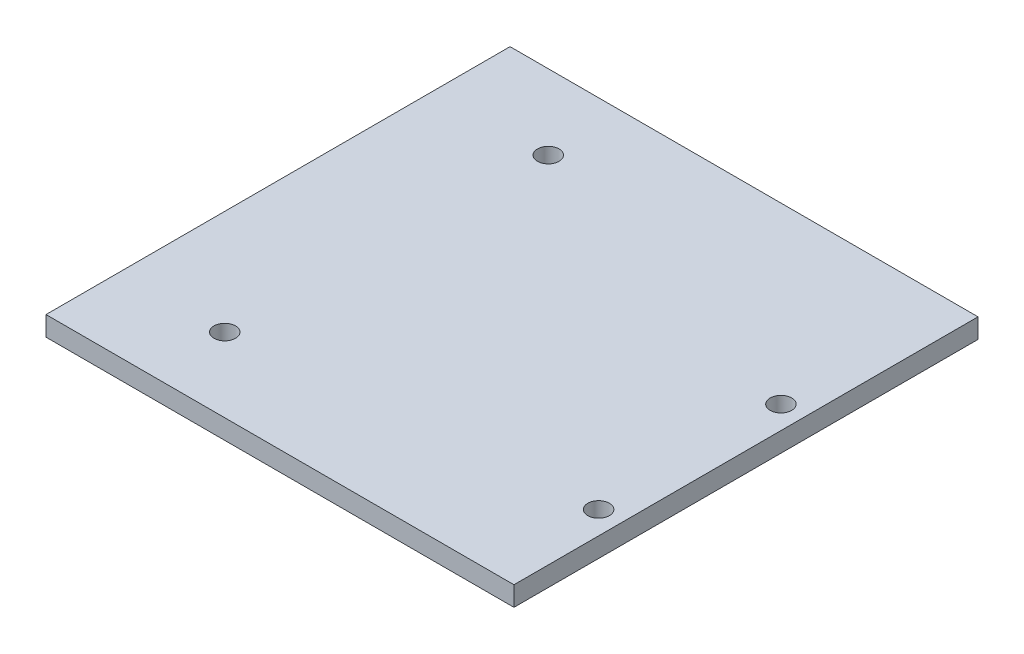
SolidWorks part; units mm, degrees
ref_plane "Front Plane" through (0, 0, 0) normal (0, 0, 1) x (1, 0, 0)
ref_plane "Top Plane" through (0, 0, 0) normal (0, 1, 0) x (1, 0, 0)
ref_plane "Right Plane" through (0, 0, 0) normal (1, 0, 0) x (0, 0, -1)
sketch "Sketch1" plane through (0, 0, 0) normal (0, 1, 0) x (1, 0, 0)
  line L1 (1.8625, 31.4168) -> (73.4625, 31.4168)
  line L2 (1.8625, 31.4168) -> (1.8625, -39.5832)
  line L3 (1.8625, -39.5832) -> (73.4625, -39.5832)
  line L4 (73.4625, 31.4168) -> (73.4625, -39.5832)
  dimension "D1" = 71.6
  dimension "D2" = 71
extrude "Boss-Extrude1" add sketch "Sketch1" along normal blind 3
sketch "Sketch2" plane through (0, 3, 0) normal (0, 1, 0) x (1, 0, 0)
  line L0 (1.8625, -39.5832) -> (17.8625, -39.5832)
  line L1 (1.8625, -39.5832) -> (73.4625, -39.5832) construction
  line L2 (1.8625, -39.5832) -> (1.8625, -31.7332)
  line L3 (1.8625, 31.4168) -> (1.8625, -39.5832) construction
  line L4 (1.8625, -31.7332) -> (1.8625, -28.2332)
  line L5 (1.8625, -28.2332) -> (1.8625, 19.9668)
  line L6 (1.8625, 31.4168) -> (19.1625, 31.4168)
  line L7 (73.4625, 31.4168) -> (1.8625, 31.4168) construction
  line L8 (19.1625, 31.4168) -> (69.9625, 31.4168)
  line L9 (17.8625, -39.5832) -> (69.9625, -39.5832)
  line L10 (73.4625, -39.5832) -> (73.4625, -31.7332)
  line L11 (73.4625, -39.5832) -> (73.4625, 31.4168) construction
  line L12 (73.4625, -31.7332) -> (73.4625, -23.1332)
  line L13 (73.4625, -23.1332) -> (73.4625, 4.7668)
  circle A0 centre (17.8625, -28.2332) radius 1.65
  circle A1 centre (19.1625, 19.9668) radius 1.65
  circle A2 centre (69.9625, -23.1332) radius 1.65
  circle A3 centre (69.9625, 4.7668) radius 1.65
  dimension "D4" = 48.2
  dimension "D6" = 50.8
  dimension "D10" = 27.9
  dimension "D1" = 16
  dimension "D2" = 7.85
  dimension "D3" = 3.5
  dimension "D5" = 17.3
  dimension "D7" = 52.1
  dimension "D8" = 7.85
  dimension "D9" = 8.6
extrude "Cut-Extrude1" cut sketch "Sketch2" against normal blind 3 contours A1 | A0 | A3 | A2
